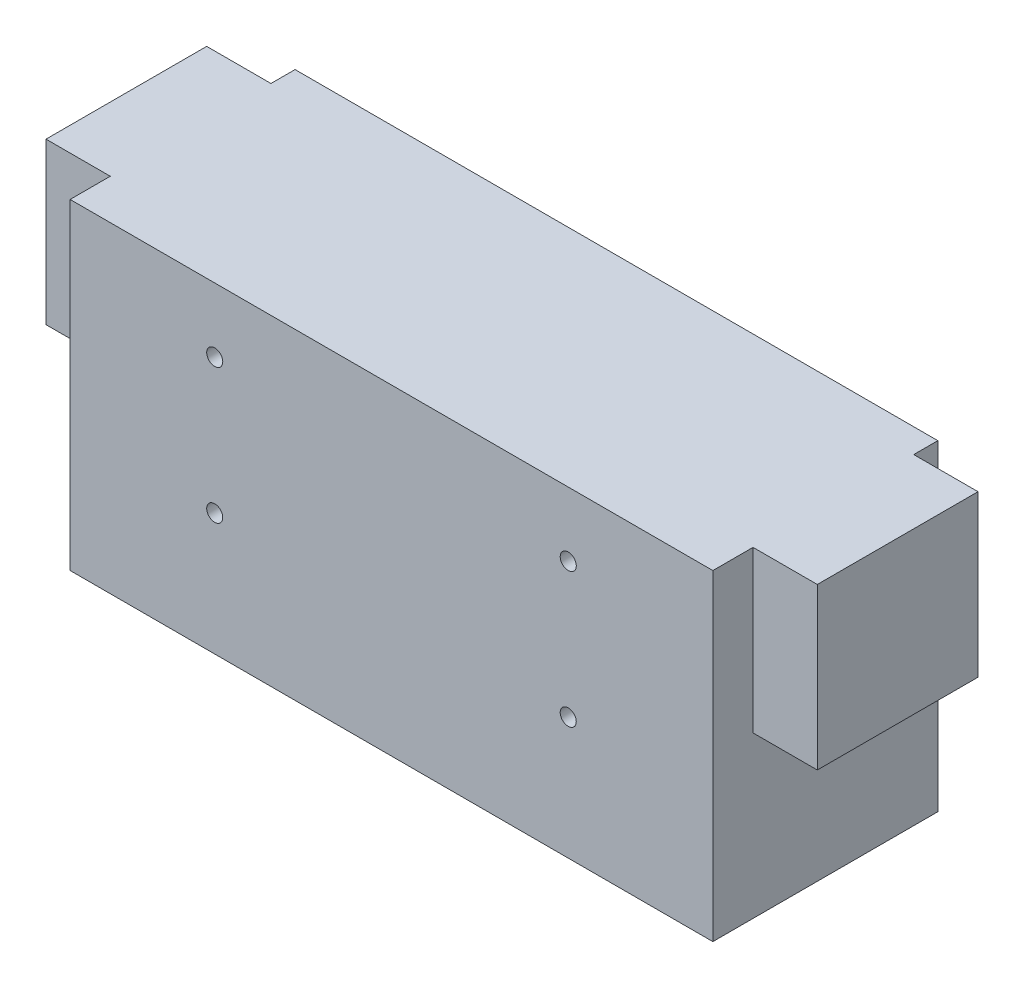
SolidWorks part; units mm, degrees
ref_plane "Front Plane" through (0, 0, 0) normal (0, 0, 1) x (1, 0, 0)
ref_plane "Top Plane" through (0, 0, 0) normal (0, 1, 0) x (1, 0, 0)
ref_plane "Right Plane" through (0, 0, 0) normal (1, 0, 0) x (0, 0, -1)
sketch "Sketch1" plane through (0, 0, 0) normal (0, 1, 0) x (1, 0, 0)
  line L0 (0, 0) -> (-62877.3227, 0) construction
  line L1 (0, 0) -> (0, -62877.3227) construction
  line L3 (-100, 35) -> (100, 35)
  line L4 (-100, 35) -> (-100, -35)
  line L5 (-100, -35) -> (100, -35)
  line L6 (100, 35) -> (100, -35)
  line L7 (-100, 35) -> (100, -35) construction
  line L8 (-100, -35) -> (100, 35) construction
  point P5 (0, 0)
  dimension "D1" = 200
  dimension "D2" = 70
extrude "Boss-Extrude1" add sketch "Sketch1" along normal blind 100 contours L4 L5 L6 L3
sketch "Sketch2" plane through (0, 100, 0) normal (0, 1, 0) x (1, 0, 0)
  line L0 (-100, 35) -> (100, 35) construction
  line L1 (0, 0) -> (0, -50000) construction
  line L2 (-100, 35) -> (-100, -35) construction
  line L3 (-120, 27.5) -> (-100, 27.5)
  line L4 (-120, 27.5) -> (-120, -22.5)
  line L5 (-120, -22.5) -> (-100, -22.5)
  line L6 (-100, 27.5) -> (-100, -22.5)
  line L7 (-120, 27.5) -> (-100, -22.5) construction
  line L8 (-120, -22.5) -> (-100, 27.5) construction
  line L9 (120, -22.5) -> (100, -22.5)
  line L10 (100, 27.5) -> (100, -22.5)
  line L11 (120, 27.5) -> (100, 27.5)
  line L12 (120, 27.5) -> (120, -22.5)
  line L13 (0, 0) -> (-50000, 0) construction
  point P5 (-110, 2.5)
  dimension "D1" = 20
  dimension "D2" = 50
  dimension "D3" = 32.5
extrude "Boss-Extrude3" add sketch "Sketch2" against normal blind 50
sketch "Sketch3" plane through (0, 0, 0) normal (0, -1, 0) x (1, 0, 0)
  line L0 (0, 0) -> (-50000, 0) construction
  line L1 (0, 0) -> (0, -50000) construction
  line L3 (65, -30) -> (90, -30)
  line L4 (65, -30) -> (65, 0)
  line L5 (65, 0) -> (90, 0)
  line L6 (90, -30) -> (90, 0)
  line L7 (65, -30) -> (90, 0) construction
  line L8 (65, 0) -> (90, -30) construction
  line L10 (-65, 0) -> (-90, 0)
  line L11 (-90, -30) -> (-90, 0)
  line L12 (-65, -30) -> (-90, -30)
  line L13 (-65, -30) -> (-65, 0)
  line L14 (-100, -35) -> (100, -35) construction
  line L15 (100, -35) -> (100, 35) construction
  point P5 (77.5, -15)
  dimension "D1" = 25
  dimension "D2" = 30
  dimension "D3" = 20
  dimension "D4" = 22.5
extrude "Cut-Extrude1" cut sketch "Sketch3" against normal blind 25
sketch "Sketch4" plane through (0, 0, -35) normal (0, 0, -1) x (-1, 0, 0)
  line L0 (0, 0) -> (0, -50000) construction
  line L1 (100, 0) -> (-100, 0) construction
  line L2 (-77.5, 0) -> (-77.5, -50000) construction
  line L3 (-100, 100) -> (-100, 0) construction
  circle A0 centre (-77.5, 12.5) radius 2.5
  circle A1 centre (77.5, 12.5) radius 2.5
  point P4 (0, 0)
  dimension "D2" = 5
  dimension "D3" = 12.5
  dimension "D1" = 22.5
extrude "Cut-Extrude2" cut sketch "Sketch4" against normal blind 15
sketch "Sketch5" plane through (0, 0, -35) normal (0, 0, -1) x (-1, 0, 0)
  line L0 (0, 0) -> (0, -50000) construction
  line L1 (100, 0) -> (-100, 0) construction
  circle A0 centre (-77.5, 12.5) radius 3.75
  circle A1 centre (77.5, 12.5) radius 3.75
  point P4 (0, 0)
  dimension "D1" = 7.5
extrude "Cut-Extrude3" cut sketch "Sketch5" against normal blind 4
sketch "Sketch6" plane through (0, 0, -27.5) normal (0, 0, -1) x (-1, 0, 0)
  line L0 (0, 0) -> (0, -50000) construction
  line L1 (-120, 75) -> (49880, 75) construction
  line L2 (-120, 50) -> (-120, 100) construction
  line L3 (-110, 50) -> (-110, -49950) construction
  line L4 (-120, 50) -> (-100, 50) construction
  circle A0 centre (-110, 87.5) radius 2
  circle A1 centre (-110, 62.5) radius 2
  circle A2 centre (110, 62.5) radius 2
  circle A3 centre (110, 87.5) radius 2
  point P7 (-120, 75)
  point P12 (-110, 50)
  dimension "D1" = 4
  dimension "D2" = 12.5
extrude "Cut-Extrude4" cut sketch "Sketch6" against normal blind 15
sketch "Sketch7" plane through (0, 0, -35) normal (0, 0, -1) x (-1, 0, 0)
  line L0 (0, 0) -> (0, -50000) construction
  line L1 (100, 50) -> (-49900, 50) construction
  line L2 (100, 100) -> (100, 0) construction
  line L3 (-77.5, 18) -> (49922.5, 18) construction
  line L5 (0, 59) -> (-50000, 59) construction
  line L6 (100, 100) -> (-100, 100) construction
  line L7 (-90, 90) -> (90, 90)
  line L8 (-90, 90) -> (-90, 28)
  line L9 (-90, 28) -> (90, 28)
  line L10 (90, 90) -> (90, 28)
  line L11 (-90, 90) -> (90, 28) construction
  line L12 (-90, 28) -> (90, 90) construction
  point P7 (100, 50)
  point P14 (0, 59)
  dimension "D1" = 32
  dimension "D2" = 41
  dimension "D3" = 180
  dimension "D4" = 62
extrude "Cut-Extrude5" cut sketch "Sketch7" against normal offset from surface (60 mm away) 10 up to face at (0, 50, 35)
sketch "Sketch8" plane through (0, 0, -35) normal (0, 0, -1) x (-1, 0, 0)
  line L0 (0, 0) -> (0, -50000) construction
  line L1 (100, 0) -> (-100, 0) construction
  line L2 (100, 100) -> (-100, 100) construction
  line L3 (-100, 100) -> (-100, 0) construction
  circle A0 centre (-45, 15) radius 2
  circle A1 centre (45, 15) radius 2
  circle A2 centre (-93, 93) radius 2
  circle A3 centre (93, 93) radius 2
  point P4 (0, 0)
  dimension "D1" = 4
  dimension "D2" = 15
  dimension "D4" = 4
  dimension "D5" = 7
  dimension "D6" = 7
  dimension "D3" = 45
extrude "Cut-Extrude6" cut sketch "Sketch8" against normal blind 15
sketch "Sketch9" plane through (0, 0, 25) normal (0, 0, -1) x (-1, 0, 0)
  line L0 (0, 0) -> (0, -50000) construction
  line L1 (-90, 59) -> (49910, 59) construction
  line L2 (-90, 28) -> (-90, 90) construction
  circle A0 centre (-55, 80) radius 2.5
  circle A1 centre (55, 80) radius 2.5
  circle A2 centre (55, 38) radius 2.5
  circle A3 centre (-55, 38) radius 2.5
  point P7 (-90, 59)
  dimension "D1" = 5
  dimension "D2" = 55
  dimension "D3" = 21
extrude "Cut-Extrude7" cut sketch "Sketch9" against normal through all
sketch "Sketch10" plane through (0, 0, 25) normal (0, 0, -1) x (-1, 0, 0)
  line L0 (0, 0) -> (0, -50000) construction
  line L1 (100, 0) -> (-100, 0) construction
  line L2 (-90, 59) -> (49910, 59) construction
  line L3 (-90, 90) -> (-90, 28) construction
  circle A1 centre (-55, 80) radius 3.75
  circle A2 centre (-55, 38) radius 3.75
  circle A3 centre (55, 38) radius 3.75
  circle A4 centre (55, 80) radius 3.75
  point P4 (0, 0)
  point P9 (-90, 59)
  dimension "D1" = 7.5
extrude "Cut-Extrude8" cut sketch "Sketch10" against normal blind 4
